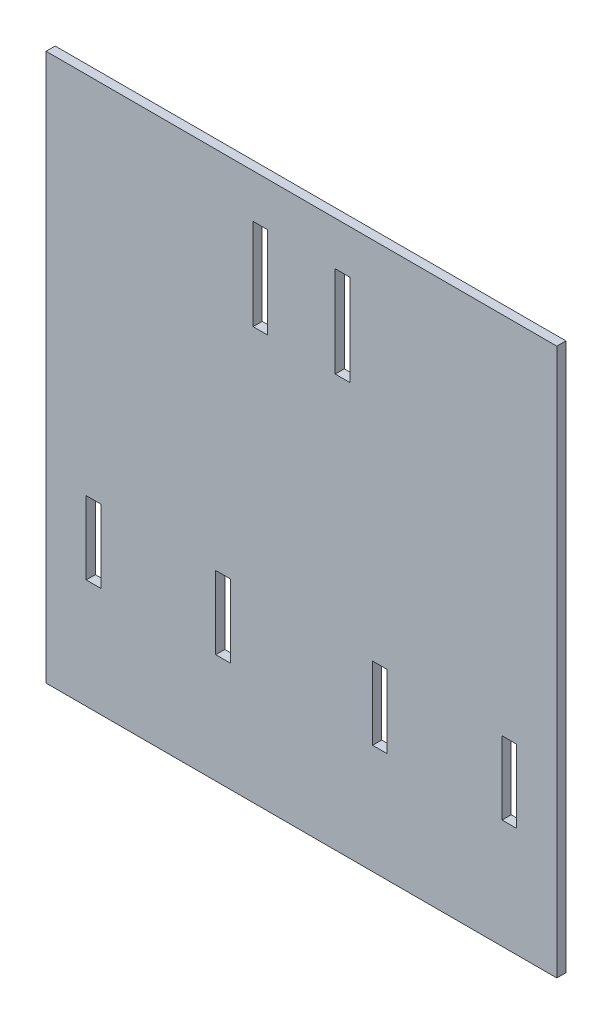
SolidWorks part; units mm, degrees
ref_plane "Front Plane" through (0, 0, 0) normal (0, 0, 1) x (1, 0, 0)
ref_plane "Top Plane" through (0, 0, 0) normal (0, 1, 0) x (1, 0, 0)
ref_plane "Right Plane" through (0, 0, 0) normal (1, 0, 0) x (0, 0, -1)
sketch "Sketch1" plane through (0, 0, 0) normal (0, 0, 1) x (1, 0, 0)
  line L1 (-140, 0) -> (140, 0)
  line L2 (-140, 0) -> (-140, 300)
  line L3 (-140, 300) -> (140, 300)
  line L4 (140, 0) -> (140, 300)
  dimension "D1" = 300
  dimension "D2" = 280
extrude "Boss-Extrude1" add sketch "Sketch1" along normal blind 5
sketch "Sketch2" plane through (0, 0, 0) normal (0, 0, -1) x (-1, 0, 0)
  line L0 (140, 0) -> (-140, 0) construction
  line L1 (-118, 100) -> (-110, 100)
  line L2 (-118, 100) -> (-118, 60)
  line L3 (-118, 60) -> (-110, 60)
  line L4 (-110, 100) -> (-110, 60)
  line L5 (-47, 100) -> (-39, 100)
  line L6 (-47, 100) -> (-47, 60)
  line L7 (-47, 60) -> (-39, 60)
  line L8 (-39, 100) -> (-39, 60)
  line L9 (39, 100) -> (47, 100)
  line L10 (39, 100) -> (39, 60)
  line L11 (39, 60) -> (47, 60)
  line L12 (47, 100) -> (47, 60)
  line L13 (110, 100) -> (118, 100)
  line L14 (110, 100) -> (110, 60)
  line L15 (110, 60) -> (118, 60)
  line L16 (118, 100) -> (118, 60)
  line L17 (0, 0) -> (0, 300) construction
  line L18 (-140, 300) -> (140, 300) construction
  line L20 (-26.5, 276) -> (-18.5, 276)
  line L21 (-26.5, 276) -> (-26.5, 226)
  line L22 (-26.5, 226) -> (-18.5, 226)
  line L23 (-18.5, 276) -> (-18.5, 226)
  line L24 (18.5, 276) -> (26.5, 276)
  line L25 (18.5, 276) -> (18.5, 226)
  line L26 (18.5, 226) -> (26.5, 226)
  line L27 (26.5, 276) -> (26.5, 226)
  point P18 (-114, 100)
  point P24 (-43, 100)
  point P25 (114, 100)
  point P26 (43, 100)
  point P27 (43, 60)
  point P28 (-43, 60)
  point P37 (22.5, 276)
  point P38 (-22.5, 276)
  point P39 (26.5, 251)
  dimension "D1" = 60
  dimension "D2" = 100
  dimension "D3" = 8
  dimension "D4" = 71
  dimension "D5" = 71
  dimension "D6" = 86
  dimension "D7" = 45
  dimension "D8" = 251
  dimension "D9" = 50
extrude "Cut-Extrude1" cut sketch "Sketch2" against normal through all
